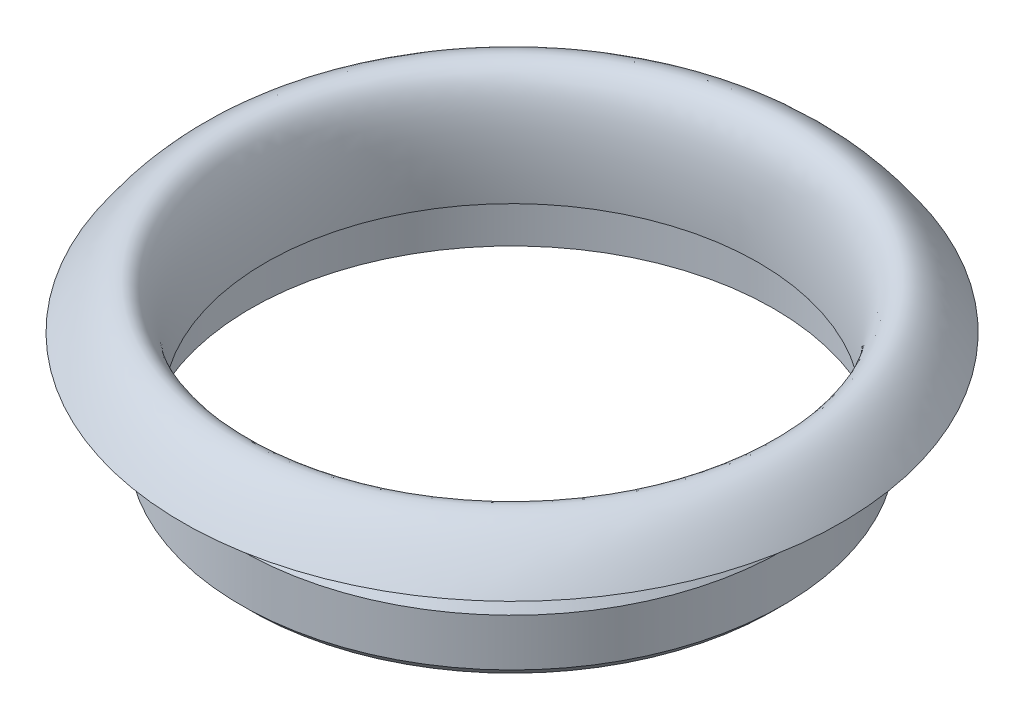
SolidWorks part; units mm, degrees
ref_plane "Front Plane" through (0, 0, 0) normal (0, 0, 1) x (1, 0, 0)
ref_plane "Top Plane" through (0, 0, 0) normal (0, 1, 0) x (1, 0, 0)
ref_plane "Right Plane" through (0, 0, 0) normal (1, 0, 0) x (0, 0, -1)
sketch "Sketch2" plane through (0, 0, 0) normal (0, 0, 1) x (1, 0, 0)
  line L0 (0, 0) -> (-90.1811, 0) construction
  line L1 (0, 0) -> (0, 80.6614) construction
  line L2 (-52, 0) -> (-52, -38.7953) construction
  line L3 (-55.2, 0) -> (-55.2, -38.7953) construction
  line L4 (-52, 0) -> (-55.2, 0)
  line L5 (-55.2, 0) -> (-55.2, -10)
  line L6 (-55.2, -10) -> (-57.2, -8)
  line L7 (-57.2, -8) -> (-57.2, 0)
  line L8 (-57.2, 2) -> (-57.2, 2)
  line L9 (-57.2, 2) -> (-57.2, 2)
  line L10 (-57.2, 2) -> (-57.2, 2)
  line L12 (-69.533, 13.2645) -> (-67.8704, 12.1529)
  line L13 (-57.2, 2) -> (-57.2, 0)
  line L14 (-57.2, 2) -> (-53.9083, 7.3273)
  line L16 (-53.9198, 2) -> (-57.2, 2) construction
  spline S0 degree 3 poles (-52, 0) (-50.7454, 25.3387) (-58.8221, 29.2845) (-69.533, 13.2645) knots 0 0 0 0 1 1 1 1
  spline S1 degree 1 poles (-53.9198, 2) (-67.8704, 12.1529) knots 0 0 1 1 construction
  spline S2 degree 3 poles (-53.9198, 2) (-53.8974, 2.7025) (-53.867, 4.1382) (-53.8719, 6.1118) (-53.9237, 7.9775) (-54.0537, 10.2949) (-54.3264, 12.8824) (-54.9727, 16.3471) (-55.8987, 18.77) (-56.8834, 20.1055) (-57.5434, 20.6165) (-58.1129, 20.8176) (-58.815, 20.8333) (-59.8224, 20.5442) (-61.1063, 19.8257) (-62.5969, 18.6357) (-64.2396, 16.9711) (-65.7111, 15.1845) (-66.9256, 13.5373) (-67.5646, 12.6102) (-67.8704, 12.1529) knots 0.026043 0.026043 0.026043 0.026043 0.056479 0.086916 0.117352 0.147788 0.20866 0.269532 0.391277 0.452149 0.513022 0.573894 0.634766 0.695639 0.756511 0.817383 0.878255 0.939128 0.969564 1 1 1 1 only from (-53.9083, 7.3273) to (-67.8704, 12.1529)
  point P19 (0, 0)
  dimension "D1" = 52
  dimension "D2" = 3.2
  dimension "D3" = 2
  dimension "D4" = 135
  dimension "D5" = 10
  dimension "D6" = 2
revolve "Revolve1" add sketch "Sketch2" angle 360 about L1
